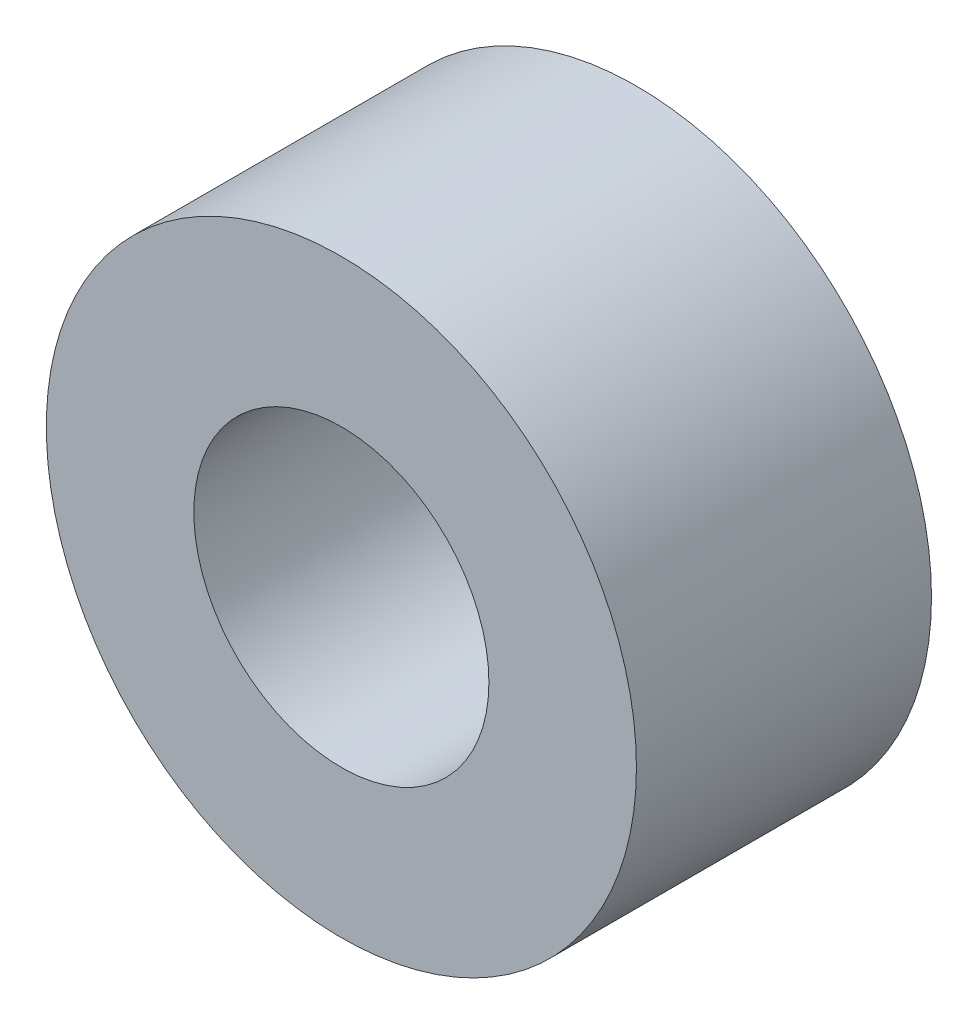
SolidWorks part; units mm, degrees
ref_plane "Alzado" through (0, 0, 0) normal (0, 0, 1) x (1, 0, 0)
ref_plane "Planta" through (0, 0, 0) normal (0, 1, 0) x (1, 0, 0)
ref_plane "Vista lateral" through (0, 0, 0) normal (1, 0, 0) x (0, 0, -1)
sketch "Croquis1" plane through (0, 0, 0) normal (0, 0, 1) x (1, 0, 0)
  circle A0 centre (0, 0) radius 10
  dimension "D1" = 20
extrude "Saliente-Extruir1" add sketch "Croquis1" along normal mid plane 10
sketch "Croquis2" plane through (0, 0, 5) normal (0, 0, 1) x (1, 0, 0)
  circle A0 centre (0, 0) radius 5
  dimension "D1" = 10
extrude "Cortar-Extruir1" cut sketch "Croquis2" against normal through all
